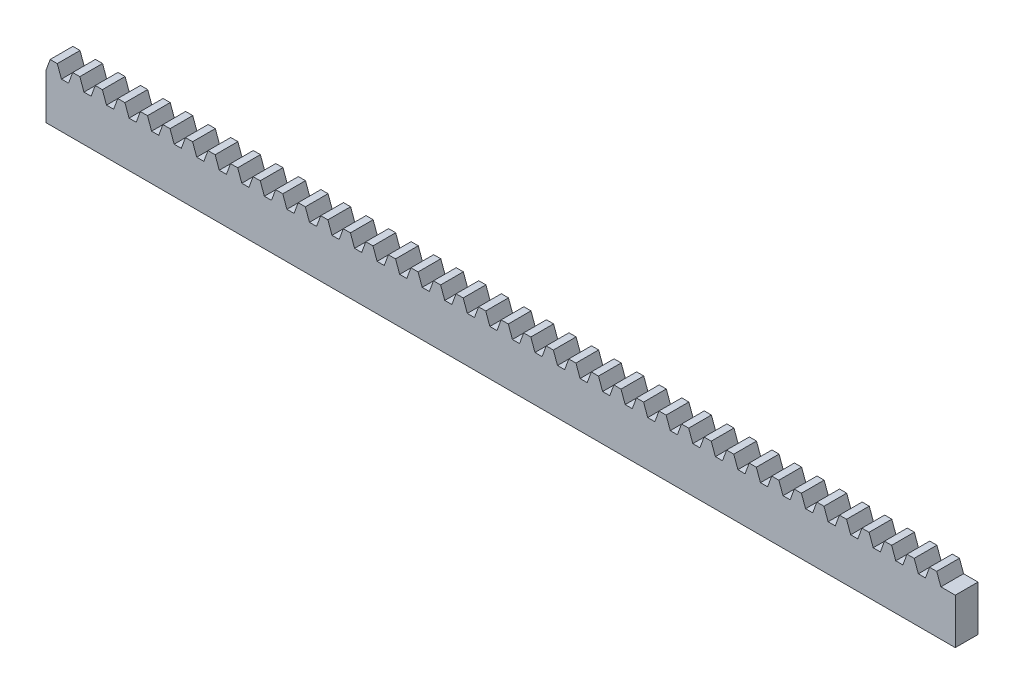
SolidWorks part; units mm, degrees
ref_plane "前视基准面" through (0, 0, 0) normal (0, 0, 1) x (1, 0, 0)
ref_plane "上视基准面" through (0, 0, 0) normal (0, 1, 0) x (1, 0, 0)
ref_plane "右视基准面" through (0, 0, 0) normal (1, 0, 0) x (0, 0, -1)
sketch "草图1" plane through (0, 0, 0) normal (0, 0, 1) x (1, 0, 0)
  line L1 (0, 0) -> (200, 0)
  line L2 (0, 0) -> (0, -10)
  line L3 (0, -10) -> (200, -10)
  line L4 (200, 0) -> (200, -10)
  dimension "D1" = 10
  dimension "L" = 200
extrude "拉伸1" add sketch "草图1" along normal blind 5
sketch "草图2" plane through (0, 0, 5) normal (0, 0, 1) x (1, 0, 0)
  line L0 (0, 0) -> (1.6379, 4.5)
  line L1 (1.6379, 4.5) -> (1.7528, 4.5)
  line L2 (1.7528, 4.5) -> (3.3906, 0)
  line L3 (200, 0) -> (0, 0) construction
  line L4 (0, 0) -> (3.3906, 0)
  line L5 (0.9099, 2.5) -> (2.4807, 2.5) construction
  line L6 (0.9099, 2.5) -> (2.4807, 2.5)
  line M4 (200, 0) -> (0, 0)
  dimension "D2" = 70
  dimension "alpha" = 110
  dimension "ha" = 2
  dimension "hf" = 2.5
  dimension "S" = 1.5708
extrude "拉伸2" add sketch "草图2" against normal up to surface (5 mm away) contours L6 L0 L2 M4 up to face at (100, -5, 0)
pattern_linear "阵列(线性)1" count 40 spacing 4.96 along (1, 0, 0) of "拉伸2"
equation "\"D2@草图2\" = 180 - \"alpha@草图2\""
